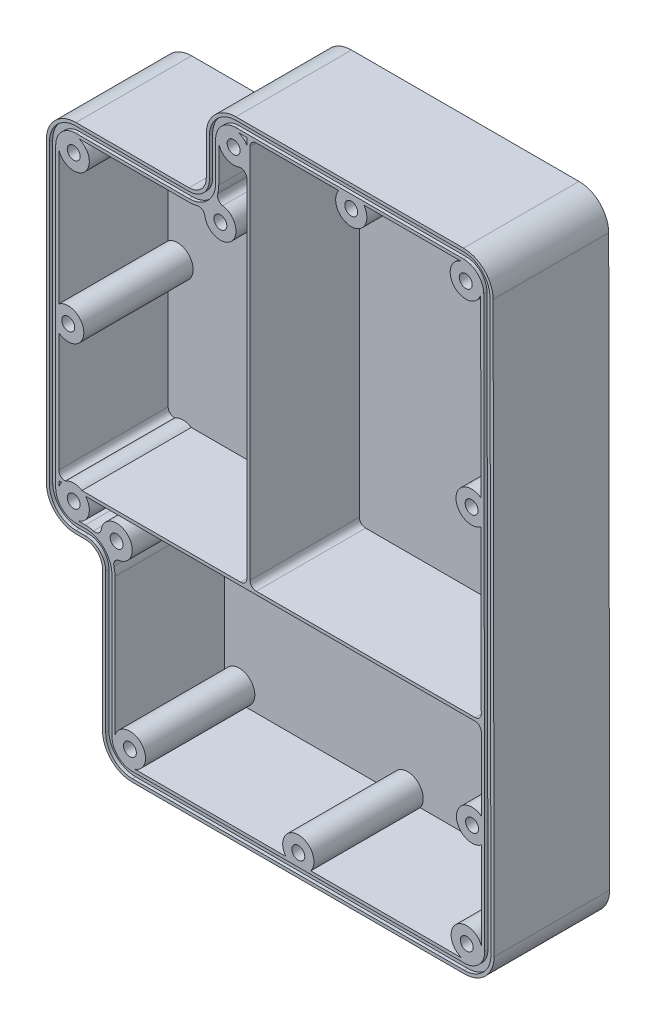
SolidWorks part; units mm, degrees
material "ABS"
ref_plane "X-Y Datum" through (0, 0, 0) normal (0, 0, 1) x (1, 0, 0)
ref_plane "X-Z Datum" through (0, 0, 0) normal (0, 1, 0) x (1, 0, 0)
ref_plane "Y-Z Datum" through (0, 0, 0) normal (1, 0, 0) x (0, 0, -1)
sketch "Sketch6" plane through (0, 0, 0) normal (0, 0, 1) x (1, 0, 0)
  line L0 (-12.5134, -74.0435) -> (88.5786, -74.0435) construction
  line L6 (-12.5134, -1.9075) -> (88.5786, -1.9075) construction
  line L7 (88.5786, -74.0435) -> (88.5786, -1.9075) construction
  line L8 (-57.9089, 111.2495) -> (4.5751, 111.2495) construction
  line L9 (-57.9089, 111.2495) -> (-57.9089, 1.9025) construction
  line L10 (-57.9089, 1.9025) -> (4.5751, 1.9025) construction
  line L11 (4.5751, 111.2495) -> (4.5751, 1.9025) construction
  line L12 (88.2023, 1.9025) -> (8.3851, 1.9025) construction
  line L13 (88.2023, 1.9025) -> (88.2023, 145.7849) construction
  line L14 (88.2023, 145.7849) -> (8.3851, 145.7849) construction
  line L15 (8.3851, 1.9025) -> (8.3851, 145.7849) construction
  line L16 (88.2023, 1.9025) -> (8.3851, 145.7849) construction
  line L17 (88.2023, 145.7849) -> (8.3851, 1.9025) construction
  line L18 (-59.1789, 112.5195) -> (5.8451, 112.5195)
  line L23 (-35.0564, -1.9075) -> (-12.5134, -1.9075) construction
  line L24 (-35.0564, -1.9075) -> (-35.0564, -74.0435) construction
  line L25 (-35.0564, -74.0435) -> (-12.5134, -74.0435) construction
  line L27 (5.8451, 112.5195) -> (5.8451, 0.6325)
  line L28 (-59.1789, 0.6325) -> (5.8451, 0.6325)
  line L29 (-59.1789, 112.5195) -> (-59.1789, 0.6325)
  line L30 (-12.5134, -0.6375) -> (89.8486, -0.6375)
  line L31 (89.8486, -75.3135) -> (89.8486, -0.6375)
  line L32 (-12.5134, -75.3135) -> (89.8486, -75.3135)
  line L33 (-36.3264, -75.3135) -> (-12.5134, -75.3135)
  line L34 (-36.3264, -0.6375) -> (-36.3264, -75.3135)
  line L35 (-36.3264, -0.6375) -> (-12.5134, -0.6375)
  line L36 (89.4723, 147.0549) -> (7.1151, 147.0549)
  line L37 (7.1151, 0.6325) -> (7.1151, 147.0549)
  line L38 (89.4723, 0.6325) -> (7.1151, 0.6325)
  line L39 (89.4723, 0.6325) -> (89.4723, 147.0549)
  circle A0 centre (-6.4174, -7.8841) radius 2.1
  circle A1 centre (82.9906, -6.8681) radius 2.1
  circle A2 centre (82.8086, -67.8271) radius 2.1
  circle A3 centre (-7.4334, -68.8441) radius 2.1
  circle A4 centre (-54.3765, 106.4235) radius 2.1
  circle A5 centre (-2.3085, 106.4425) radius 2.1
  circle A6 centre (-2.4335, 6.7285) radius 2.1
  circle A7 centre (-54.3765, 6.7285) radius 2.1
  circle A8 centre (48.2937, 118.2849) radius 27.5
  circle A9 centre (48.347, 29.3848) radius 27.5
  circle A10 centre (38.1604, 73.8437) radius 6.477
  circle A11 centre (58.4804, 73.826) radius 6.477
  circle A12 centre (14.8621, 92.914) radius 6.477
  circle A13 centre (20.3804, 73.8592) radius 2.4
  circle A14 centre (76.2603, 73.8105) radius 2.4
  point P43 (48.2937, 73.8437)
  dimension "D1" = 109.347
  dimension "D2" = 62.484
  dimension "D3" = 79.8172
  dimension "D4" = 143.8823
  dimension "D5" = 101.092
  dimension "D6" = 72.136
  dimension "D10" = 1.27
  dimension "D11" = 1.27
  dimension "D7" = 1.27
  dimension "D8" = 1.27
  dimension "D9" = 1.27
sketch "Sketch7" plane through (0, 0, 0) normal (0, 0, 1) x (1, 0, 0)
  line L1 (89.4723, 147.0549) -> (89.8486, -75.3135) construction
  line L2 (89.8486, -75.3135) -> (-36.3264, -75.3135) construction
  line L3 (-36.3264, -75.3135) -> (-36.3264, 0.6325) construction
  line L4 (-59.1789, 0.6325) -> (5.8451, 0.6325) construction
  line L5 (-36.3264, 0.6325) -> (-59.1789, 0.6325) construction
  line L6 (-59.1789, 0.6325) -> (-59.1789, 112.5195) construction
  line L7 (-59.1789, 112.5195) -> (5.8451, 112.5195) construction
  line L8 (5.8451, 112.5195) -> (5.8451, 147.0549) construction
  line L10 (5.8451, 147.0549) -> (89.4723, 147.0549) construction
  line L11 (1.4001, 161.0249) -> (93.9098, 161.0249)
  line L12 (103.4348, 151.516) -> (103.8261, -79.7424)
  line L13 (94.3011, -89.2835) -> (-40.7714, -89.2835)
  line L14 (-50.2964, -79.7585) -> (-50.2964, -22.8625)
  line L15 (-59.8214, -13.3375) -> (-63.6239, -13.3375)
  line L16 (-73.1489, -3.8125) -> (-73.1489, 116.9645)
  line L17 (-63.6239, 126.4895) -> (-17.6499, 126.4895)
  line L18 (-8.1249, 136.0145) -> (-8.1249, 151.4999)
  line L19 (48.2937, 147.0549) -> (48.2937, 154.6749) construction
  line L20 (5.8451, 147.0549) -> (0.4569, 152.443) construction
  line L21 (89.4723, 147.0549) -> (94.8604, 152.443) construction
  line L22 (5.8451, 112.5195) -> (0.4569, 117.9077) construction
  line L23 (-59.1789, 112.5195) -> (-64.5671, 117.9077) construction
  line L24 (-59.1789, 0.6325) -> (-64.5671, -4.7556) construction
  line L25 (-36.3264, 0.6325) -> (-41.7146, -4.7556) construction
  line L26 (-36.3264, -75.3135) -> (-41.7146, -80.7016) construction
  line L27 (26.7611, -75.3135) -> (26.7611, -82.9335) construction
  line L28 (89.8486, -75.3135) -> (95.2368, -80.7016) construction
  line L29 (89.7853, -37.8829) -> (97.4053, -37.8829) construction
  line L30 (89.5958, 74.0591) -> (97.2158, 74.0591) construction
  line L31 (-59.1789, 56.576) -> (-66.7989, 56.576) construction
  line L32 (103.4187, 161.0249) -> (103.8423, -89.2835) construction
  line L33 (103.8423, -89.2835) -> (-50.2964, -89.2835) construction
  line L34 (-50.2964, -89.2835) -> (-50.2964, -13.3375) construction
  line L35 (-50.2964, -13.3375) -> (-73.1489, -13.3375) construction
  line L36 (-73.1489, -13.3375) -> (-73.1489, 126.4895) construction
  line L37 (-73.1489, 126.4895) -> (-8.1249, 126.4895) construction
  line L38 (-8.1249, 126.4895) -> (-8.1249, 161.0249) construction
  line L39 (-8.1249, 161.0249) -> (103.4187, 161.0249) construction
  circle A0 centre (94.8604, 152.443) radius 6.35 construction
  circle A1 centre (48.2937, 154.6749) radius 6.35 construction
  circle A2 centre (0.4569, 152.443) radius 6.35 construction
  circle A3 centre (0.4569, 117.9077) radius 6.35 construction
  circle A4 centre (-64.5671, 117.9077) radius 6.35 construction
  circle A5 centre (-66.7989, 56.576) radius 6.35 construction
  circle A6 centre (-64.5671, -4.7556) radius 6.35 construction
  circle A7 centre (-41.7146, -4.7556) radius 6.35 construction
  circle A8 centre (-41.7146, -80.7016) radius 6.35 construction
  circle A9 centre (26.7611, -82.9335) radius 6.35 construction
  circle A10 centre (95.2368, -80.7016) radius 6.35 construction
  circle A11 centre (97.4053, -37.8829) radius 6.35 construction
  circle A12 centre (97.2158, 74.0591) radius 6.35 construction
  arc A13 (103.8261, -79.7424) -> (94.3011, -89.2835) centre (94.3011, -79.7585) cw
  arc A14 (-40.7714, -89.2835) -> (-50.2964, -79.7585) centre (-40.7714, -79.7585) cw
  arc A15 (-50.2964, -22.8625) -> (-59.8214, -13.3375) centre (-59.8214, -22.8625) ccw
  arc A16 (-63.6239, -13.3375) -> (-73.1489, -3.8125) centre (-63.6239, -3.8125) cw
  arc A17 (-73.1489, 116.9645) -> (-63.6239, 126.4895) centre (-63.6239, 116.9645) cw
  arc A18 (-17.6499, 126.4895) -> (-8.1249, 136.0145) centre (-17.6499, 136.0145) ccw
  arc A19 (93.9098, 161.0249) -> (103.4348, 151.516) centre (93.9098, 151.4999) cw
  arc A20 (1.4001, 161.0249) -> (-8.1249, 151.4999) centre (1.4001, 151.4999) ccw
  dimension "D2" = 9.525
  dimension "D1" = 13.97
extrude "Boss-Extrude1" add sketch "Sketch7" along normal blind 44.45
shell "Shell1" thickness 2.54
sketch "Sketch8" plane through (0, 0, 44.45) normal (0, 0, 1) x (1, 0, 0)
  line L72 (-8.1249, 151.4999) -> (-8.1249, 136.0145)
  line L73 (93.9098, 161.0249) -> (1.4001, 161.0249)
  line L74 (103.8261, -79.7424) -> (103.4348, 151.516)
  line L75 (-40.7714, -89.2835) -> (94.3011, -89.2835)
  line L76 (-50.2964, -22.8625) -> (-50.2964, -79.7585)
  line L77 (-63.6239, -13.3375) -> (-59.8214, -13.3375)
  line L78 (-73.1489, 116.9645) -> (-73.1489, -3.8125)
  line L79 (-9.3949, 151.4999) -> (-9.3949, 136.0145)
  line L80 (93.9098, 162.2949) -> (1.4001, 162.2949)
  line L81 (105.0961, -79.7402) -> (104.7047, 151.5181)
  line L82 (-40.7714, -90.5535) -> (94.3011, -90.5535)
  line L83 (-51.5664, -22.8625) -> (-51.5664, -79.7585)
  line L84 (-63.6239, -14.6075) -> (-59.8214, -14.6075)
  line L85 (-74.4189, 116.9645) -> (-74.4189, -3.8125)
  line L86 (-17.6499, 127.7595) -> (-63.6239, 127.7595)
  line L87 (-9.3949, 151.4999) -> (-9.3949, 136.0145)
  line L88 (93.9098, 162.2949) -> (1.4001, 162.2949)
  line L89 (105.0961, -79.7402) -> (104.7047, 151.5181)
  line L90 (-40.7714, -90.5535) -> (94.3011, -90.5535)
  line L91 (-51.5664, -22.8625) -> (-51.5664, -79.7585)
  line L92 (-63.6239, -14.6075) -> (-59.8214, -14.6075)
  line L93 (-74.4189, 116.9645) -> (-74.4189, -3.8125)
  line L94 (-17.6499, 127.7595) -> (-63.6239, 127.7595)
  line L95 (-17.6499, 126.4895) -> (-63.6239, 126.4895)
  arc A65 (-17.6499, 126.4895) -> (-8.1249, 136.0145) centre (-17.6499, 136.0145) ccw
  arc A66 (1.4001, 161.0249) -> (-8.1249, 151.4999) centre (1.4001, 151.4999) ccw
  arc A67 (103.4348, 151.516) -> (93.9098, 161.0249) centre (93.9098, 151.4999) ccw
  arc A68 (94.3011, -89.2835) -> (103.8261, -79.7424) centre (94.3011, -79.7585) ccw
  arc A69 (-50.2964, -79.7585) -> (-40.7714, -89.2835) centre (-40.7714, -79.7585) ccw
  arc A70 (-50.2964, -22.8625) -> (-59.8214, -13.3375) centre (-59.8214, -22.8625) ccw
  arc A71 (-73.1489, -3.8125) -> (-63.6239, -13.3375) centre (-63.6239, -3.8125) ccw
  arc A72 (-63.6239, 126.4895) -> (-73.1489, 116.9645) centre (-63.6239, 116.9645) ccw
  arc A73 (-17.6499, 127.7595) -> (-9.3949, 136.0145) centre (-17.6499, 136.0145) ccw
  arc A74 (1.4001, 162.2949) -> (-9.3949, 151.4999) centre (1.4001, 151.4999) ccw
  arc A75 (104.7047, 151.5181) -> (93.9098, 162.2949) centre (93.9098, 151.4999) ccw
  arc A76 (94.3011, -90.5535) -> (105.0961, -79.7402) centre (94.3011, -79.7585) ccw
  arc A77 (-51.5664, -79.7585) -> (-40.7714, -90.5535) centre (-40.7714, -79.7585) ccw
  arc A78 (-51.5664, -22.8625) -> (-59.8214, -14.6075) centre (-59.8214, -22.8625) ccw
  arc A79 (-74.4189, -3.8125) -> (-63.6239, -14.6075) centre (-63.6239, -3.8125) ccw
  arc A80 (-63.6239, 127.7595) -> (-74.4189, 116.9645) centre (-63.6239, 116.9645) ccw
  arc A81 (-17.6499, 127.7595) -> (-9.3949, 136.0145) centre (-17.6499, 136.0145) ccw
  arc A82 (1.4001, 162.2949) -> (-9.3949, 151.4999) centre (1.4001, 151.4999) ccw
  arc A83 (104.7047, 151.5181) -> (93.9098, 162.2949) centre (93.9098, 151.4999) ccw
  arc A84 (94.3011, -90.5535) -> (105.0961, -79.7402) centre (94.3011, -79.7585) ccw
  arc A85 (-51.5664, -79.7585) -> (-40.7714, -90.5535) centre (-40.7714, -79.7585) ccw
  arc A86 (-51.5664, -22.8625) -> (-59.8214, -14.6075) centre (-59.8214, -22.8625) ccw
  arc A87 (-74.4189, -3.8125) -> (-63.6239, -14.6075) centre (-63.6239, -3.8125) ccw
  arc A88 (-63.6239, 127.7595) -> (-74.4189, 116.9645) centre (-63.6239, 116.9645) ccw
  dimension "D1" = 1.27
  dimension "D2" = 1.27
extrude "Cut-Extrude1" cut sketch "Sketch8" against normal blind 1.3208
sketch "Sketch9" plane through (0, 0, 0) normal (0, 0, 1) x (1, 0, 0)
  line L30 (-40.7714, -88.0135) -> (94.3011, -88.0135)
  line L31 (-49.0264, -22.8625) -> (-49.0264, -79.7585)
  line L32 (-63.6239, -12.0675) -> (-59.8214, -12.0675)
  line L33 (-71.8789, 116.9645) -> (-71.8789, -3.8125)
  line L34 (-17.6499, 125.2195) -> (-63.6239, 125.2195)
  line L35 (-40.7714, -88.0135) -> (94.3011, -88.0135)
  line L36 (-49.0264, -22.8625) -> (-49.0264, -79.7585)
  line L37 (-63.6239, -12.0675) -> (-59.8214, -12.0675)
  line L38 (-71.8789, 116.9645) -> (-71.8789, -3.8125)
  line L39 (-17.6499, 125.2195) -> (-63.6239, 125.2195)
  line L47 (-40.7714, -89.2835) -> (94.3011, -89.2835)
  line L48 (103.8261, -79.7424) -> (103.4348, 151.516)
  line L49 (93.9098, 161.0249) -> (1.4001, 161.0249)
  line L50 (-6.8549, 151.4999) -> (-6.8549, 136.0145)
  line L51 (93.9098, 159.7549) -> (1.4001, 159.7549)
  line L52 (102.5561, -79.7445) -> (102.1648, 151.5138)
  line L53 (-6.8549, 151.4999) -> (-6.8549, 136.0145)
  line L54 (93.9098, 159.7549) -> (1.4001, 159.7549)
  line L55 (102.5561, -79.7445) -> (102.1648, 151.5138)
  line L56 (-8.1249, 151.4999) -> (-8.1249, 136.0145)
  line L57 (-17.6499, 126.4895) -> (-63.6239, 126.4895)
  line L58 (-73.1489, 116.9645) -> (-73.1489, -3.8125)
  line L59 (-63.6239, -13.3375) -> (-59.8214, -13.3375)
  line L60 (-50.2964, -22.8625) -> (-50.2964, -79.7585)
  arc A24 (-49.0264, -79.7585) -> (-40.7714, -88.0135) centre (-40.7714, -79.7585) ccw
  arc A25 (-49.0264, -22.8625) -> (-59.8214, -12.0675) centre (-59.8214, -22.8625) ccw
  arc A26 (-71.8789, -3.8125) -> (-63.6239, -12.0675) centre (-63.6239, -3.8125) ccw
  arc A27 (-63.6239, 125.2195) -> (-71.8789, 116.9645) centre (-63.6239, 116.9645) ccw
  arc A28 (-49.0264, -79.7585) -> (-40.7714, -88.0135) centre (-40.7714, -79.7585) ccw
  arc A29 (-49.0264, -22.8625) -> (-59.8214, -12.0675) centre (-59.8214, -22.8625) ccw
  arc A30 (-71.8789, -3.8125) -> (-63.6239, -12.0675) centre (-63.6239, -3.8125) ccw
  arc A31 (-63.6239, 125.2195) -> (-71.8789, 116.9645) centre (-63.6239, 116.9645) ccw
  arc A44 (94.3011, -89.2835) -> (103.8261, -79.7424) centre (94.3011, -79.7585) ccw
  arc A45 (103.4348, 151.516) -> (93.9098, 161.0249) centre (93.9098, 151.4999) ccw
  arc A46 (1.4001, 161.0249) -> (-8.1249, 151.4999) centre (1.4001, 151.4999) ccw
  arc A47 (-17.6499, 126.4895) -> (-8.1249, 136.0145) centre (-17.6499, 136.0145) ccw
  arc A48 (-17.6499, 125.2195) -> (-6.8549, 136.0145) centre (-17.6499, 136.0145) ccw
  arc A49 (1.4001, 159.7549) -> (-6.8549, 151.4999) centre (1.4001, 151.4999) ccw
  arc A50 (102.1648, 151.5138) -> (93.9098, 159.7549) centre (93.9098, 151.4999) ccw
  arc A51 (94.3011, -88.0135) -> (102.5561, -79.7445) centre (94.3011, -79.7585) ccw
  arc A52 (-17.6499, 125.2195) -> (-6.8549, 136.0145) centre (-17.6499, 136.0145) ccw
  arc A53 (1.4001, 159.7549) -> (-6.8549, 151.4999) centre (1.4001, 151.4999) ccw
  arc A54 (102.1648, 151.5138) -> (93.9098, 159.7549) centre (93.9098, 151.4999) ccw
  arc A55 (94.3011, -88.0135) -> (102.5561, -79.7445) centre (94.3011, -79.7585) ccw
  arc A56 (-63.6239, 126.4895) -> (-73.1489, 116.9645) centre (-63.6239, 116.9645) ccw
  arc A57 (-73.1489, -3.8125) -> (-63.6239, -13.3375) centre (-63.6239, -3.8125) ccw
  arc A58 (-50.2964, -22.8625) -> (-59.8214, -13.3375) centre (-59.8214, -22.8625) ccw
  arc A59 (-50.2964, -79.7585) -> (-40.7714, -89.2835) centre (-40.7714, -79.7585) ccw
  dimension "D1" = 1.27
  dimension "D2" = 1.27
  dimension "D3" = 1.27
extrude "Boss-Extrude2" add sketch "Sketch9" along normal up to surface (43.1292 mm away) up to face at (-6.9849, 46.2251, 43.1292)
sketch "Sketch10" plane through (0, 0, 0) normal (0, 0, 1) x (1, 0, 0)
  line L50 (-47.7564, -22.8625) -> (-47.7564, -79.7585)
  line L51 (-63.6239, -10.7975) -> (-59.8214, -10.7975)
  line L52 (-70.6089, 116.9645) -> (-70.6089, -3.8125)
  line L53 (-17.6499, 123.9495) -> (-63.6239, 123.9495)
  line L54 (-5.5849, 151.4999) -> (-5.5849, 136.0145)
  line L55 (93.9098, 158.4849) -> (1.4001, 158.4849)
  line L56 (-47.7564, -22.8625) -> (-47.7564, -79.7585)
  line L57 (-63.6239, -10.7975) -> (-59.8214, -10.7975)
  line L58 (-70.6089, 116.9645) -> (-70.6089, -3.8125)
  line L59 (-17.6499, 123.9495) -> (-63.6239, 123.9495)
  line L60 (-5.5849, 151.4999) -> (-5.5849, 136.0145)
  line L61 (93.9098, 158.4849) -> (1.4001, 158.4849)
  line L70 (-40.7714, -88.0135) -> (94.3011, -88.0135)
  line L71 (102.5561, -79.7445) -> (102.1648, 151.5138)
  line L72 (101.2861, -79.7466) -> (100.8948, 151.5117)
  line L73 (-40.7714, -86.7435) -> (94.3011, -86.7435)
  line L74 (101.2861, -79.7466) -> (100.8948, 151.5117)
  line L75 (-40.7714, -86.7435) -> (94.3011, -86.7435)
  line L76 (93.9098, 159.7549) -> (1.4001, 159.7549)
  line L77 (-6.8549, 151.4999) -> (-6.8549, 136.0145)
  line L78 (-17.6499, 125.2195) -> (-63.6239, 125.2195)
  line L79 (-71.8789, 116.9645) -> (-71.8789, -3.8125)
  line L80 (-63.6239, -12.0675) -> (-59.8214, -12.0675)
  line L81 (-49.0264, -22.8625) -> (-49.0264, -79.7585)
  arc A49 (-47.7564, -79.7585) -> (-40.7714, -86.7435) centre (-40.7714, -79.7585) ccw
  arc A50 (-47.7564, -22.8625) -> (-59.8214, -10.7975) centre (-59.8214, -22.8625) ccw
  arc A51 (-70.6089, -3.8125) -> (-63.6239, -10.7975) centre (-63.6239, -3.8125) ccw
  arc A52 (-63.6239, 123.9495) -> (-70.6089, 116.9645) centre (-63.6239, 116.9645) ccw
  arc A53 (-17.6499, 123.9495) -> (-5.5849, 136.0145) centre (-17.6499, 136.0145) ccw
  arc A54 (1.4001, 158.4849) -> (-5.5849, 151.4999) centre (1.4001, 151.4999) ccw
  arc A55 (-47.7564, -79.7585) -> (-40.7714, -86.7435) centre (-40.7714, -79.7585) ccw
  arc A56 (-47.7564, -22.8625) -> (-59.8214, -10.7975) centre (-59.8214, -22.8625) ccw
  arc A57 (-70.6089, -3.8125) -> (-63.6239, -10.7975) centre (-63.6239, -3.8125) ccw
  arc A58 (-63.6239, 123.9495) -> (-70.6089, 116.9645) centre (-63.6239, 116.9645) ccw
  arc A59 (-17.6499, 123.9495) -> (-5.5849, 136.0145) centre (-17.6499, 136.0145) ccw
  arc A60 (1.4001, 158.4849) -> (-5.5849, 151.4999) centre (1.4001, 151.4999) ccw
  arc A67 (-49.0264, -79.7585) -> (-40.7714, -88.0135) centre (-40.7714, -79.7585) ccw
  arc A68 (94.3011, -88.0135) -> (102.5561, -79.7445) centre (94.3011, -79.7585) ccw
  arc A69 (100.8948, 151.5117) -> (93.9098, 158.4849) centre (93.9098, 151.4999) ccw
  arc A70 (94.3011, -86.7435) -> (101.2861, -79.7466) centre (94.3011, -79.7585) ccw
  arc A71 (100.8948, 151.5117) -> (93.9098, 158.4849) centre (93.9098, 151.4999) ccw
  arc A72 (94.3011, -86.7435) -> (101.2861, -79.7466) centre (94.3011, -79.7585) ccw
  arc A73 (102.1648, 151.5138) -> (93.9098, 159.7549) centre (93.9098, 151.4999) ccw
  arc A74 (1.4001, 159.7549) -> (-6.8549, 151.4999) centre (1.4001, 151.4999) ccw
  arc A75 (-17.6499, 125.2195) -> (-6.8549, 136.0145) centre (-17.6499, 136.0145) ccw
  arc A76 (-63.6239, 125.2195) -> (-71.8789, 116.9645) centre (-63.6239, 116.9645) ccw
  arc A77 (-71.8789, -3.8125) -> (-63.6239, -12.0675) centre (-63.6239, -3.8125) ccw
  arc A78 (-49.0264, -22.8625) -> (-59.8214, -12.0675) centre (-59.8214, -22.8625) ccw
  dimension "D1" = 1.27
  dimension "D2" = 1.27
  dimension "D3" = 1.27
extrude "Boss-Extrude3" add sketch "Sketch10" along normal up to surface (44.45 mm away) up to face at (-7.3682, 46.2253, 44.45)
sketch "Sketch11" plane through (0, 0, 0) normal (0, 0, 1) x (1, 0, 0)
  line L0 (-41.7146, -4.7556) -> (-47.1027, -10.1438) construction
  line L1 (0.4569, 117.9077) -> (-4.9312, 123.2958) construction
  line L2 (42.4873, 158.4849) -> (55.1295, 158.4849)
  line L3 (93.9098, 158.4849) -> (1.4001, 158.4849) construction
  line L4 (1.4001, 158.4849) -> (93.9098, 158.4849) construction
  line L5 (-71.8789, 60.386) -> (-71.8789, 52.766)
  line L7 (22.9511, -88.0135) -> (30.5711, -88.0135)
  line L9 (102.4788, -34.0643) -> (102.4917, -41.6843)
  line L11 (102.2894, 77.8777) -> (102.3023, 70.2578)
  circle A0 centre (0.4569, 152.443) radius 6.35
  circle A1 centre (48.2937, 154.6749) radius 6.35
  circle A2 centre (94.8604, 152.443) radius 6.35
  arc A3 (102.2894, 77.8777) -> (102.3023, 70.2578) centre (97.2158, 74.0591) ccw
  arc A4 (102.4788, -34.0643) -> (102.4917, -41.6843) centre (97.4053, -37.8829) ccw
  circle A5 centre (95.2368, -80.7016) radius 6.35
  arc A6 (30.5711, -88.0135) -> (22.9511, -88.0135) centre (26.7611, -82.9335) ccw
  circle A7 centre (-41.7146, -80.7016) radius 6.35
  circle A8 centre (-64.5671, -4.7556) radius 6.35
  circle A9 centre (-47.1027, -10.1438) radius 6.35
  arc A10 (-71.8789, 52.766) -> (-71.8789, 60.386) centre (-66.7989, 56.576) ccw
  circle A11 centre (-64.5671, 117.9077) radius 6.35
  circle A12 centre (-4.9312, 123.2958) radius 6.35
  circle A13 centre (0.4569, 152.443) radius 2.625
  circle A14 centre (48.2937, 154.6749) radius 2.625
  circle A15 centre (94.8604, 152.443) radius 2.625
  circle A16 centre (-4.9312, 123.2958) radius 2.625
  circle A17 centre (-64.5671, 117.9077) radius 2.625
  circle A18 centre (-66.7989, 56.576) radius 2.625
  circle A19 centre (-64.5671, -4.7556) radius 2.625
  circle A20 centre (-41.7146, -80.7016) radius 2.625
  circle A21 centre (26.7611, -82.9335) radius 2.625
  circle A22 centre (95.2368, -80.7016) radius 2.625
  circle A23 centre (97.4053, -37.8829) radius 2.625
  circle A24 centre (97.2158, 74.0591) radius 2.625
  circle A25 centre (-47.1027, -10.1438) radius 2.625
  line M3 (101.2861, -79.7466) -> (100.8948, 151.5117)
  arc M4 (100.8948, 151.5117) -> (93.9098, 158.4849) centre (93.9098, 151.4999) ccw
  line M5 (93.9098, 158.4849) -> (1.4001, 158.4849)
  arc M6 (1.4001, 158.4849) -> (-5.5849, 151.4999) centre (1.4001, 151.4999) ccw
  line M7 (-5.5849, 151.4999) -> (-5.5849, 136.0145)
  line M9 (-17.6499, 123.9495) -> (-63.6239, 123.9495)
  arc M10 (-63.6239, 123.9495) -> (-70.6089, 116.9645) centre (-63.6239, 116.9645) ccw
  line M11 (-70.6089, 116.9645) -> (-70.6089, -3.8125)
  arc M12 (-70.6089, -3.8125) -> (-63.6239, -10.7975) centre (-63.6239, -3.8125) ccw
  line M13 (-63.6239, -10.7975) -> (-59.8214, -10.7975)
  line M15 (-47.7564, -22.8625) -> (-47.7564, -79.7585)
  arc M16 (-47.7564, -79.7585) -> (-40.7714, -86.7435) centre (-40.7714, -79.7585) ccw
  line M17 (-40.7714, -86.7435) -> (94.3011, -86.7435)
  arc M18 (94.3011, -86.7435) -> (101.2861, -79.7466) centre (94.3011, -79.7585) ccw
extrude "Boss-Extrude4" add sketch "Sketch11" along direction (0, 0, -1) on the side of the normal up to surface (44.45 mm away) contours A0 M7 M5 M6 | L2 A1 | A2 M5 M3 M4 | A3 M3 | A4 M3 | A5 M3 M17 M18 | A6 M17 | A7 M17 M15 M16 | A9 | A8 M13 M11 M12 | A10 M11 | A11 M11 M9 M10 | A12
sketch "Sketch12" plane through (0, 0, 0) normal (0, 0, 1) x (1, 0, 0)
  line L0 (7.1151, 147.0549) -> (7.1151, 158.4849) construction
  line L1 (2.4111, 158.4849) -> (43.2137, 158.4849) construction
  line L2 (-12.5134, -0.6375) -> (89.8486, -0.6375) construction
  line L3 (7.1151, 158.4849) -> (5.8451, 158.4849)
  line L4 (7.1151, 158.4849) -> (7.1151, 0.6325)
  line L5 (7.1151, -0.6375) -> (5.8451, -0.6375)
  line L6 (5.8451, 158.4849) -> (5.8451, 0.6325)
  line L7 (-59.1789, 0.6325) -> (-70.6089, 0.6325) construction
  line L8 (-70.6089, 51.496) -> (-70.6089, -2.8015) construction
  line L9 (101.0344, 68.9856) -> (101.2067, -32.7965) construction
  line L10 (-70.6089, 0.6325) -> (5.8451, 0.6325)
  line L11 (-70.6089, 0.6325) -> (-70.6089, -0.6375)
  line L12 (-70.6089, -0.6375) -> (101.1522, -0.6375)
  line L13 (101.1522, 0.6325) -> (101.1522, -0.6375)
  line L14 (7.1151, 0.6325) -> (101.1522, 0.6325)
extrude "Boss-Extrude5" add sketch "Sketch12" along normal up to surface (44.45 mm away) contours L4 L14 L13 L12 L11 L10 L6 L3
fillet "Fillet1" radius 2.54 11 edges at (-7.8986, 128.9098, 22.225) (-10.5452, 126.2632, 22.225) (-52.7167, -13.1112, 22.225) (-50.0701, -15.7578, 22.225) (-70.6089, 0.6325, 22.225) (101.1501, 0.6325, 22.225) (101.1522, -0.6375, 22.225) (5.8451, 149.0829, 22.225) (7.1151, 158.4849, 22.225) (7.1151, 0.6325, 22.225) (5.8451, 0.6325, 22.225)
